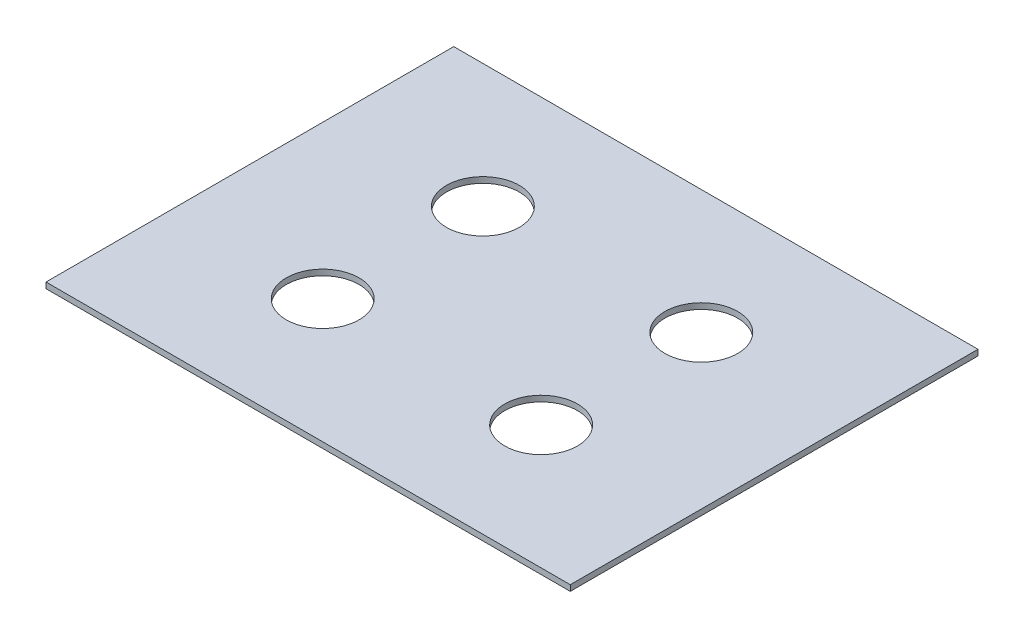
SolidWorks part; units mm, degrees
ref_plane "Front Plane" through (0, 0, 0) normal (0, 0, 1) x (1, 0, 0)
ref_plane "Top Plane" through (0, 0, 0) normal (0, 1, 0) x (1, 0, 0)
ref_plane "Right Plane" through (0, 0, 0) normal (1, 0, 0) x (0, 0, -1)
sketch "Sketch1" plane through (0, 0, 0) normal (0, 1, 0) x (1, 0, 0)
  line L1 (-114.3, 88.9) -> (114.3, 88.9)
  line L2 (-114.3, 88.9) -> (-114.3, -88.9)
  line L3 (-114.3, -88.9) -> (114.3, -88.9)
  line L4 (114.3, 88.9) -> (114.3, -88.9)
  line L5 (-114.3, 88.9) -> (114.3, -88.9) construction
  line L6 (-114.3, -88.9) -> (114.3, 88.9) construction
  point P0 (0, 0)
  dimension "D1" = 177.8
  dimension "D2" = 228.6
extrude "Boss-Extrude1" add sketch "Sketch1" along normal blind 2.54
sketch "Sketch2" plane through (0, 2.54, 0) normal (0, 1, 0) x (1, 0, 0)
  line L1 (-63.5, 50.8) -> (63.5, 50.8) construction
  line L2 (-63.5, 50.8) -> (-63.5, -50.8) construction
  line L3 (-63.5, -50.8) -> (63.5, -50.8) construction
  line L4 (63.5, 50.8) -> (63.5, -50.8) construction
  line L5 (-63.5, 50.8) -> (63.5, -50.8) construction
  line L6 (-63.5, -50.8) -> (63.5, 50.8) construction
  circle A0 centre (-47.625, 34.925) radius 15.875
  circle A1 centre (47.625, 34.925) radius 15.875
  circle A2 centre (47.625, -34.925) radius 15.875
  circle A3 centre (-47.625, -34.925) radius 15.875
  point P0 (0, 0)
  dimension "D3" = 31.75
  dimension "D1" = 127
  dimension "D2" = 101.6
extrude "Cut-Extrude1" cut sketch "Sketch2" against normal through all
